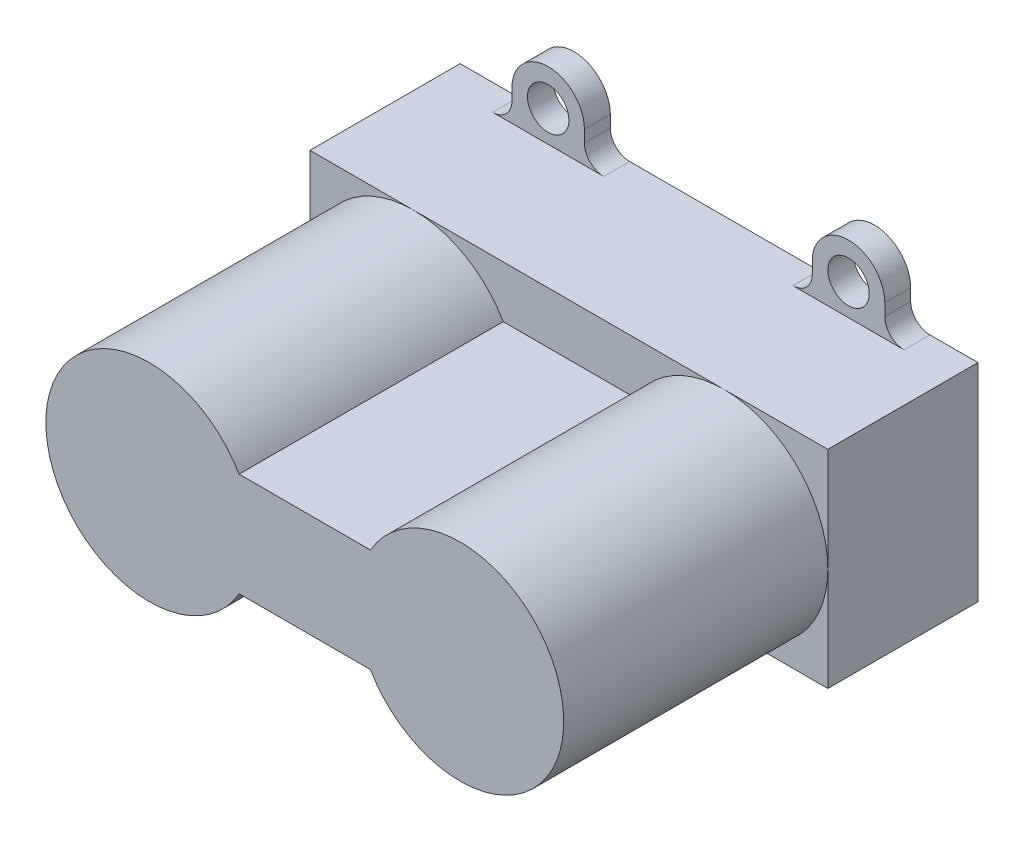
SolidWorks part; units mm, degrees
ref_plane "Plan de face" through (0, 0, 0) normal (0, 0, 1) x (1, 0, 0)
ref_plane "Plan de dessus" through (0, 0, 0) normal (0, 1, 0) x (1, 0, 0)
ref_plane "Plan de droite" through (0, 0, 0) normal (1, 0, 0) x (0, 0, -1)
sketch "Esquisse1" plane through (0, 0, 0) normal (0, 0, 1) x (1, 0, 0)
  line L0 (-25, -10) -> (-19.3642, -10)
  line L1 (-25, -10) -> (-25, 10)
  line L2 (25, -10) -> (25, 10)
  line L3 (-25, 10) -> (-19.3642, 10)
  line L4 (-25, -10) -> (25, 10) construction
  line L5 (25, -10) -> (-25, 10) construction
  line L6 (-17.5, 13) -> (-17.5, 11.8642)
  line L7 (-10.5, 13) -> (-10.5, 11.8642)
  line L8 (11.5, 13) -> (11.5, 11.8642)
  line L9 (18.5, 13) -> (18.5, 11.8642)
  line L10 (-17.5, -13) -> (-17.5, -11.8642)
  line L11 (-10.5, -13) -> (-10.5, -11.8642)
  line L12 (11.5, -13) -> (11.5, -11.8642)
  line L13 (18.5, -13) -> (18.5, -11.8642)
  line L14 (-8.6358, -10) -> (9.6358, -10)
  line L15 (20.3642, -10) -> (25, -10)
  line L16 (-8.6358, 10) -> (9.6358, 10)
  line L17 (20.3642, 10) -> (25, 10)
  circle A0 centre (-14, 13) radius 2
  circle A1 centre (15, 13) radius 2
  circle A2 centre (-14, -13) radius 2
  circle A3 centre (15, -13) radius 2
  arc A4 (-10.5, 13) -> (-17.5, 13) centre (-14, 13) ccw
  arc A5 (18.5, 13) -> (11.5, 13) centre (15, 13) ccw
  arc A6 (-17.5, -13) -> (-10.5, -13) centre (-14, -13) ccw
  arc A7 (11.5, -13) -> (18.5, -13) centre (15, -13) ccw
  arc A8 (-17.5, 11.8642) -> (-19.3642, 10) centre (-19.3642, 11.8642) cw
  arc A9 (-10.5, 11.8642) -> (-8.6358, 10) centre (-8.6358, 11.8642) ccw
  arc A10 (11.5, 11.8642) -> (9.6358, 10) centre (9.6358, 11.8642) cw
  arc A11 (18.5, 11.8642) -> (20.3642, 10) centre (20.3642, 11.8642) ccw
  arc A12 (20.3642, -10) -> (18.5, -11.8642) centre (20.3642, -11.8642) ccw
  arc A13 (9.6358, -10) -> (11.5, -11.8642) centre (9.6358, -11.8642) cw
  arc A14 (-8.6358, -10) -> (-10.5, -11.8642) centre (-8.6358, -11.8642) ccw
  arc A15 (-17.5, -11.8642) -> (-19.3642, -10) centre (-19.3642, -11.8642) ccw
  point P1 (0, 0)
  point P16 (-17.5, 10)
  point P35 (-10.5, 10)
  point P38 (11.5, 10)
  point P41 (18.5, 10)
  point P44 (18.5, -10)
  point P47 (11.5, -10)
  point P50 (-10.5, -10)
  dimension "D3" = 4
  dimension "D4" = 7
  dimension "D9" = 1.8642
  dimension "D1" = 50
  dimension "D2" = 20
  dimension "D5" = 29
  dimension "D6" = 11
  dimension "D7" = 3
  dimension "D8" = 3
extrude "Boss.-Extru.1" add sketch "Esquisse1" along normal blind 14.5
sketch "Esquisse3" plane through (25, 0, 0) normal (1, 0, 0) x (0, 0, -1)
  line L0 (-14.5, 10) -> (0, 10) construction
  line L1 (-14.5, 10) -> (0, 10)
  line L2 (-14.5, -10) -> (0, -10) construction
  line L3 (-14.5, -10) -> (0, -10)
  line L4 (-14.5, -10) -> (-14.5, -16.5)
  line L5 (-14.5, -16.5) -> (-2.5, -16.5)
  line L6 (-14.5, -16.5) -> (0, -16.5) construction
  line L7 (-2.5, -16.5) -> (-2.5, -10)
  line L8 (-14.5, 10) -> (-14.5, 16.5)
  line L9 (-14.5, 16.5) -> (-2.5, 16.5)
  line L10 (0, 16.5) -> (-14.5, 16.5) construction
  line L11 (-2.5, 16.5) -> (-2.5, 10)
  line L12 (0, 11.8642) -> (0, 13) construction
  line M6 (-14.5, -10) -> (0, -10)
  dimension "D1" = 2.5
extrude "Enlèv. mat.-Extru.1" cut sketch "Esquisse3" against normal through all contours L11 L9 L8 L1 | L5 L7 L4 M6
sketch "Esquisse4" plane through (0, 0, 14.5) normal (0, 0, 1) x (1, 0, 0)
  line L0 (25, 10) -> (-25, 10) construction
  line L1 (-25, -10) -> (25, -10) construction
  line L2 (-25, 10) -> (-25, -10) construction
  line L3 (25, -10) -> (25, 10) construction
  line L4 (-6.3397, -5) -> (6.3397, -5)
  line L7 (-6.3397, 5) -> (6.3397, 5)
  arc A0 (-6.3397, 5) -> (-6.3397, -5) centre (-15, 0) ccw
  arc A1 (6.3397, -5) -> (6.3397, 5) centre (15, 0) ccw
  point P13 (0, 0)
  dimension "D1" = 10
  dimension "D2" = 5
extrude "Boss.-Extru.2" add sketch "Esquisse4" along normal blind 25.5
